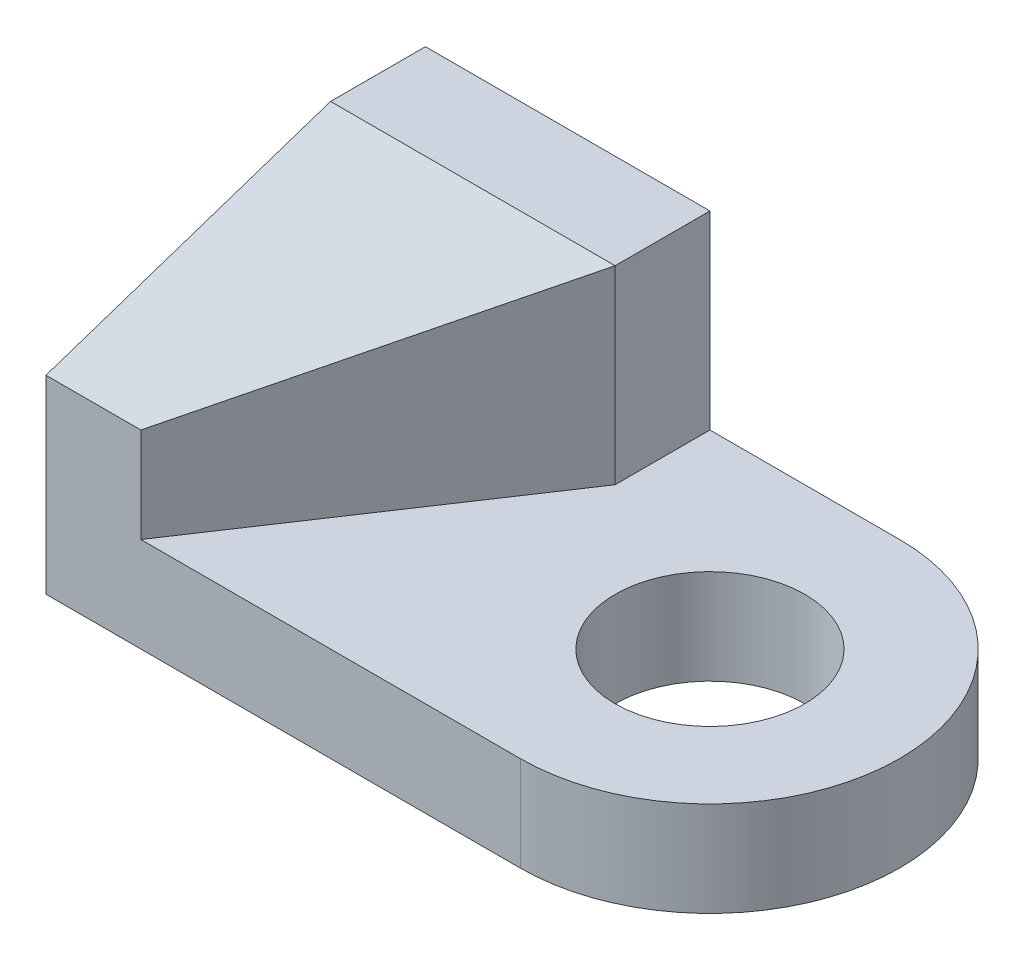
SolidWorks part; units mm, degrees
ref_plane "前基準面" through (0, 0, 0) normal (0, 0, 1) x (1, 0, 0)
ref_plane "上基準面" through (0, 0, 0) normal (0, 1, 0) x (1, 0, 0)
ref_plane "右基準面" through (0, 0, 0) normal (1, 0, 0) x (0, 0, -1)
sketch "草圖1" plane through (0, 0, 0) normal (0, 1, 0) x (1, 0, 0)
  line L1 (0, 0) -> (25, 0)
  line L2 (0, 0) -> (0, -20)
  line L3 (0, -20) -> (25, -20)
  arc A0 (25, 0) -> (25, -20) centre (25, -10) cw
  circle A1 centre (25, -10) radius 5
  dimension "D3" = 10
  dimension "D1" = 20
  dimension "D2" = 25
extrude "填料-伸長1" add sketch "草圖1" along normal blind 5
sketch "草圖2" plane through (0, 0, 0) normal (-1, 0, 0) x (0, 0, 1)
  line L0 (0, 5) -> (20, 5) construction
  line L1 (5, 5) -> (20, 5)
  line L2 (5, 5) -> (5, 15)
  line L4 (20, 5) -> (20, 10)
  line L5 (5, 15) -> (20, 10)
  dimension "D1" = 5
  dimension "D2" = 10
  dimension "D3" = 15
extrude "填料-伸長2" add sketch "草圖2" against normal blind 5
sketch "草圖3" plane through (0, 5, 0) normal (0, 1, 0) x (1, 0, 0)
  line L0 (25, 0) -> (0, 0) construction
  line L1 (0, -5) -> (15, -5)
  line L2 (0, -5) -> (0, 0)
  line L3 (0, 0) -> (15, 0)
  line L4 (15, -5) -> (15, 0)
  dimension "D1" = 5
  dimension "D2" = 15
extrude "填料-伸長3" add sketch "草圖3" along normal blind 10
sketch "草圖4" plane through (0, 5, 0) normal (0, 1, 0) x (1, 0, 0)
  line L0 (5, -20) -> (0, -20) construction
  line L1 (5, -5) -> (0, -5) construction
  line L2 (5, -5) -> (15, -5) construction
  line L3 (0, -20) -> (0, -5) construction
  line L4 (5, -20) -> (0, -20)
  line L5 (5, -5) -> (0, -5)
  line L6 (5, -5) -> (15, -5)
  line L7 (0, -20) -> (0, -5)
  line L8 (15, -5) -> (5, -20)
extrude "填料-伸長4" add sketch "草圖4" along normal blind 10
sketch "草圖5" plane through (0, 0, 0) normal (-1, 0, 0) x (0, 0, 1)
  line L0 (5, 15) -> (20, 10) construction
  line L1 (20, 15) -> (20, 0) construction
  line L2 (0, 15) -> (20, 15) construction
  line L3 (5, 15) -> (20, 10)
  line L4 (20, 15) -> (20, 10)
  line L5 (5, 15) -> (20, 15)
extrude "除料-伸長1" cut sketch "草圖5" against normal blind 22
